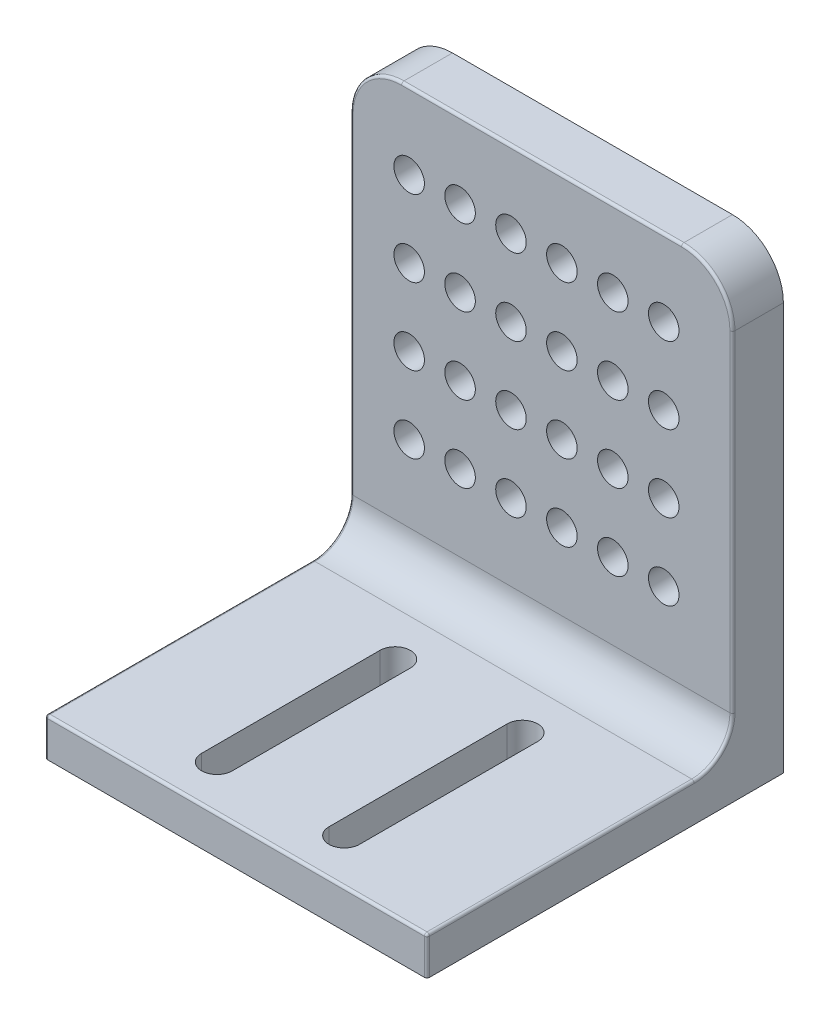
SolidWorks part; units mm, degrees
ref_plane "Front Plane" through (0, 0, 0) normal (0, 0, 1) x (1, 0, 0)
ref_plane "Top Plane" through (0, 0, 0) normal (0, 1, 0) x (1, 0, 0)
ref_plane "Right Plane" through (0, 0, 0) normal (1, 0, 0) x (0, 0, -1)
sketch "Sketch1" plane through (0, 0, 0) normal (0, 0, 1) x (1, 0, 0)
  line L1 (-37.5, 45) -> (37.5, 45)
  line L2 (-37.5, 45) -> (-37.5, -45)
  line L3 (-37.5, -45) -> (37.5, -45)
  line L4 (37.5, 45) -> (37.5, -45)
  line L5 (0, -45) -> (0, 45) construction
  line L6 (-37.5, 0) -> (37.5, 0) construction
  point P0 (0, 0)
  dimension "D1" = 75
  dimension "D2" = 90
extrude "Boss-Extrude1" add sketch "Sketch1" along normal blind 10
sketch "Sketch2" plane through (0, 0, 0) normal (0, 0, 1) x (1, 0, 0)
  circle A2 centre (23.9994, 30) radius 3
  circle A4 centre (13.9994, 30) radius 3
  circle A5 centre (3.9994, 30) radius 3
  circle A6 centre (-6.0006, 30) radius 3
  circle A7 centre (-16.0006, 30) radius 3
  circle A8 centre (-26.0006, 30) radius 3
  circle A9 centre (13.9994, 15) radius 3
  circle A10 centre (3.9994, 15) radius 3
  circle A11 centre (-6.0006, 15) radius 3
  circle A12 centre (-16.0006, 15) radius 3
  circle A13 centre (-26.0006, 15) radius 3
  circle A14 centre (13.9994, 0) radius 3
  circle A15 centre (3.9994, 0) radius 3
  circle A16 centre (-6.0006, 0) radius 3
  circle A17 centre (-16.0006, 0) radius 3
  circle A18 centre (-26.0006, 0) radius 3
  circle A19 centre (13.9994, -15) radius 3
  circle A20 centre (3.9994, -15) radius 3
  circle A21 centre (-6.0006, -15) radius 3
  circle A22 centre (-16.0006, -15) radius 3
  circle A23 centre (-26.0006, -15) radius 3
  circle A29 centre (23.9994, 15) radius 3
  circle A30 centre (23.9994, 0) radius 3
  circle A31 centre (23.9994, -15) radius 3
  dimension "D1" = 6
  dimension "D2" = 4
fillet "Fillet1" radius 10 2 edges at (37.5, 45, 5) (-37.5, 45, 5)
sketch "Sketch3" plane through (0, 0, 10) normal (0, 0, 1) x (1, 0, 0)
  line L0 (-37.5, 35) -> (-37.5, -45) construction
  line L1 (-37.5, -37.5) -> (37.5, -37.5)
  line L2 (-37.5, -37.5) -> (-37.5, -45)
  line L3 (-37.5, -45) -> (37.5, -45)
  line L4 (37.5, -37.5) -> (37.5, -45)
  dimension "D1" = 7.5
extrude "Boss-Extrude2" add sketch "Sketch3" along normal blind 60
fillet "Fillet2" radius 7.5 1 edges at (0, -37.5, 10)
extrude "Cut-Extrude1" cut sketch "Sketch2" along normal blind 10
sketch "Sketch4" plane through (0, -37.5, 0) normal (0, 1, 0) x (1, 0, 0)
  line L4 (-12.5, -26.25) -> (-12.5, -61.25) construction
  line L5 (-9.5, -26.25) -> (-9.5, -61.25)
  line L6 (-15.5, -26.25) -> (-15.5, -61.25)
  line L7 (12.5, -26.25) -> (12.5, -61.25) construction
  line L8 (9.5, -26.25) -> (9.5, -61.25)
  line L9 (15.5, -26.25) -> (15.5, -61.25)
  arc A0 (-9.5, -26.25) -> (-15.5, -26.25) centre (-12.5, -26.25) ccw
  arc A1 (-15.5, -61.25) -> (-9.5, -61.25) centre (-12.5, -61.25) ccw
  arc A2 (9.5, -26.25) -> (15.5, -26.25) centre (12.5, -26.25) cw
  arc A3 (15.5, -61.25) -> (9.5, -61.25) centre (12.5, -61.25) cw
  point P10 (-12.5, -43.75)
  point P17 (12.5, -43.75)
  dimension "D1" = 35
  dimension "D2" = 6
  dimension "D3" = 25
  dimension "D4" = 6
extrude "Cut-Extrude2" cut sketch "Sketch4" against normal blind 10
fillet "Fillet3" radius 0.5 1 edges at (0, -37.5, 70)
fillet "Fillet4" radius 0.5 13 edges at (37.5, -41.5, 70) (37.5, -37.6464, 69.8536) (-37.5, -41.5, 70) (-37.5, -37.6464, 69.8536) (-37.5, -37.5, 43.5) (-37.5, -35.3033, 12.1967) (-37.5, 2.5, 10) (-34.5711, 42.0711, 10) (0, 45, 10) (34.5711, 42.0711, 10) (37.5, 2.5, 10) (37.5, -35.3033, 12.1967) (37.5, -37.5, 43.5)
